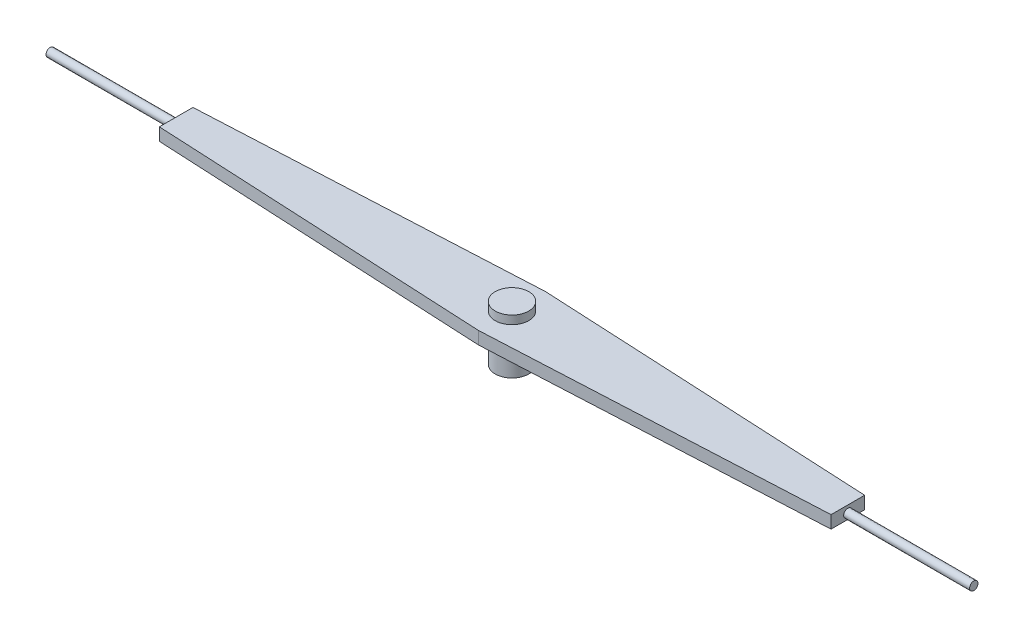
SolidWorks part; units mm, degrees
ref_plane "Front Plane" through (0, 0, 0) normal (0, 0, 1) x (1, 0, 0)
ref_plane "Top Plane" through (0, 0, 0) normal (0, 1, 0) x (1, 0, 0)
ref_plane "Right Plane" through (0, 0, 0) normal (1, 0, 0) x (0, 0, -1)
sketch "Sketch1" plane through (0, 0, 0) normal (0, 1, 0) x (1, 0, 0)
  line L0 (200, 10) -> (0, 20)
  line L1 (-200, -10) -> (200, -10)
  line L2 (-200, -10) -> (-200, 10)
  line L3 (-200, 10) -> (200, 10)
  line L4 (200, -10) -> (200, 10)
  line L5 (-200, -10) -> (200, 10) construction
  line L6 (-200, 10) -> (200, -10) construction
  line L7 (0, 20) -> (-200, 10)
  line L8 (200, -10) -> (0, -20)
  line L9 (0, -20) -> (-200, -10)
  point P0 (0, 0)
  dimension "D1" = 400
  dimension "D2" = 20
  dimension "D3" = 20
  dimension "D4" = 40
  dimension "D5" = 20
extrude "Boss-Extrude1" add sketch "Sketch1" along normal blind 7.5 contours L1 L4 L3 L2 | L0 L7 L3 | L9 L8 L1
sketch "Sketch2" plane through (200, 0, 0) normal (1, 0, 0) x (0, 0, -1)
  circle A0 centre (0, 3.2963) radius 2.5
  dimension "D1" = 5
extrude "Boss-Extrude2" add sketch "Sketch2" along normal blind 75
sketch "Sketch3" plane through (-200, 0, 0) normal (-1, 0, 0) x (0, 0, 1)
  circle A0 centre (0, 3.4691) radius 2.5
  dimension "D1" = 5
extrude "Boss-Extrude3" add sketch "Sketch3" along normal blind 75
sketch "Sketch5" plane through (0, 7.5, 0) normal (0, 1, 0) x (1, 0, 0)
  circle A0 centre (0, 0) radius 10
  dimension "D1" = 20
extrude "Boss-Extrude4" add sketch "Sketch5" along normal blind 5
sketch "Sketch6" plane through (0, 0, 0) normal (0, -1, 0) x (1, 0, 0)
  circle A0 centre (0, 0) radius 10
  dimension "D1" = 20
extrude "Boss-Extrude5" add sketch "Sketch6" along normal blind 20
sketch "Sketch7" plane through (0, -20, 0) normal (0, -1, 0) x (-1, 0, 0)
  circle A0 centre (0, 0) radius 8
extrude "Cut-Extrude1" cut sketch "Sketch7" against normal blind 15
